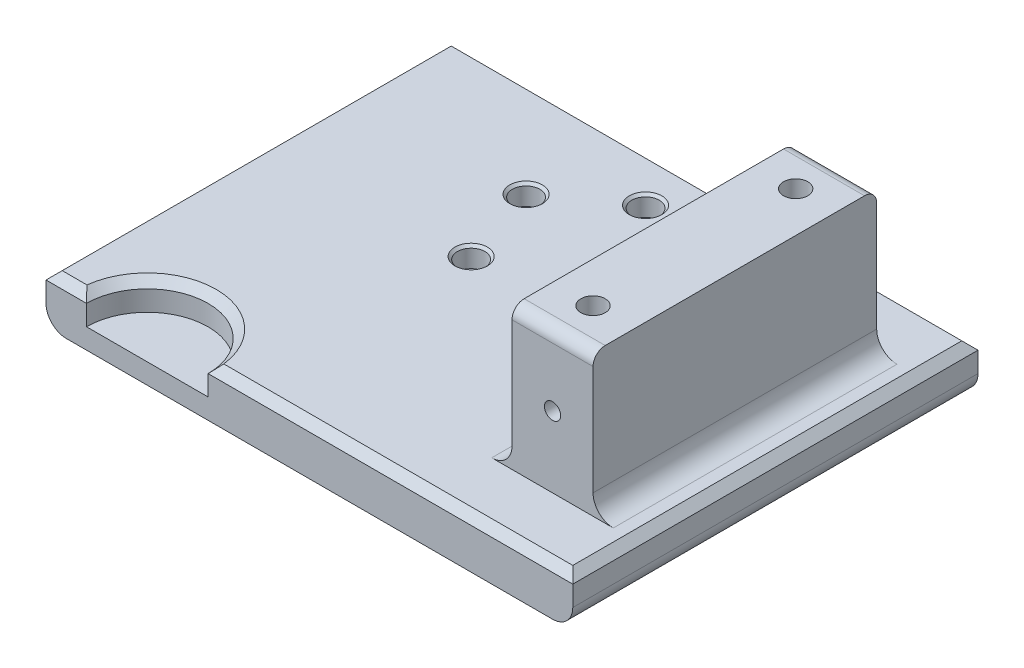
SolidWorks part; units mm, degrees
ref_plane "Front Plane" through (0, 0, 0) normal (0, 0, 1) x (1, 0, 0)
ref_plane "Top Plane" through (0, 0, 0) normal (0, 1, 0) x (1, 0, 0)
ref_plane "Right Plane" through (0, 0, 0) normal (1, 0, 0) x (0, 0, -1)
sketch "Sketch1" plane through (0, 0, 0) normal (0, 1, 0) x (1, 0, 0)
  line L1 (0, 0) -> (130, 0)
  line L2 (0, 0) -> (0, 100)
  line L3 (0, 100) -> (130, 100)
  line L4 (130, 0) -> (130, 100)
  dimension "D1" = 100
  dimension "D2" = 130
extrude "Boss-Extrude1" add sketch "Sketch1" along normal blind 12
sketch "Sketch2" plane through (0, 12, 0) normal (0, 1, 0) x (1, 0, 0)
  line L0 (0, 100) -> (0, 0) construction
  line L1 (60, 90) -> (132, 90)
  line L2 (60, 90) -> (60, 78)
  line L3 (60, 78) -> (132, 78)
  line L4 (132, 90) -> (132, 78)
  line L6 (130, 100) -> (0, 100) construction
  line L7 (130, 0) -> (130, 100) construction
  line L8 (46, 53) -> (118, 53)
  line L9 (46, 53) -> (46, 41)
  line L10 (46, 41) -> (118, 41)
  line L11 (118, 53) -> (118, 41)
  line L12 (96, 90) -> (96, 41) construction
  line L13 (78, 71.5) -> (114, 71.5)
  line L14 (78, 71.5) -> (78, 59.5)
  line L15 (78, 59.5) -> (114, 59.5)
  line L16 (114, 71.5) -> (114, 59.5)
  point P20 (96, 71.5)
  dimension "D1" = 60
  dimension "D2" = 72
  dimension "D3" = 10
  dimension "D4" = 12
  dimension "D5" = 12
  dimension "D6" = 72
  dimension "D7" = 25
  dimension "D8" = 12
  dimension "D9" = 6.5
  dimension "D10" = 6.5
  dimension "D11" = 18
sketch "Sketch3" plane through (0, 12, 0) normal (0, 1, 0) x (1, 0, 0)
  line L0 (0, 0) -> (130, 0) construction
  line L1 (10, 0) -> (40, 0)
  arc A0 (10, 0) -> (40, 0) centre (25, 0) cw
  dimension "D1" = 15
  dimension "D2" = 25
extrude "Cut-Extrude1" cut sketch "Sketch3" against normal blind 7
sketch "Sketch4" plane through (0, 12, 0) normal (0, 1, 0) x (1, 0, 0)
  line L0 (130, 100) -> (0, 100) construction
  line L1 (100, 85) -> (120, 85)
  line L2 (100, 85) -> (100, 15)
  line L3 (100, 15) -> (120, 15)
  line L4 (120, 85) -> (120, 15)
  line L5 (40, 0) -> (130, 0) construction
  line L6 (130, 0) -> (130, 100) construction
  dimension "D1" = 15
  dimension "D2" = 15
  dimension "D3" = 10
  dimension "D4" = 20
extrude "Boss-Extrude2" add sketch "Sketch4" along normal blind 35
ref_plane "Plane1" through (110, 0, 0) normal (-1, 0, 0) x (0, 0, 1)
sketch "Sketch5" plane through (110, 0, 0) normal (-1, 0, 0) x (0, 0, 1)
  line L0 (-85, 29.5) -> (-15, 29.5) construction
  line L1 (-85, 47) -> (-85, 12) construction
  line L2 (-15, 47) -> (-15, 12) construction
  line L4 (-85, 29.5) -> (-60, 29.5)
  line L5 (-85, 29.5) -> (-85, 37.5)
  line L6 (-85, 37.5) -> (-60, 37.5)
  line L7 (-60, 29.5) -> (-60, 37.5)
  line L8 (-60, 33.5) -> (-35, 33.5)
  line L9 (-60, 33.5) -> (-60, 29.5)
  line L10 (-60, 29.5) -> (-35, 29.5)
  line L11 (-35, 33.5) -> (-35, 29.5)
  line L12 (-35, 31.5) -> (-15, 31.5)
  line L13 (-35, 31.5) -> (-35, 29.5)
  line L14 (-35, 29.5) -> (-15, 29.5)
  line L15 (-15, 31.5) -> (-15, 29.5)
  dimension "D1" = 8
  dimension "D2" = 25
  dimension "D3" = 25
revolve "Cut-Revolve1" cut sketch "Sketch5" angle 360 about L0
fillet "Fillet1" radius 5 2 edges at (120, 12, -50) (100, 12, -50)
chamfer "Chamfer1" distance 2 angle 45 6 edges at (130, 12, -50) (65, 12, -100) (0, 12, -50) (5, 12, 0) (25, 12, -15) (85, 12, 0)
sketch "Sketch6" plane through (0, 12, 0) normal (0, 1, 0) x (1, 0, 0)
  line L0 (60, 70) -> (60, 87.9551) construction
  line L1 (60, 87.9551) -> (60, 70) construction
  line L2 (60, 70) -> (42.9237, 75.5484) construction
  line L3 (60, 70) -> (49.4463, 55.4741) construction
  line L4 (60, 70) -> (70.5537, 55.4741) construction
  line L5 (60, 70) -> (77.0763, 75.5484) construction
  line L6 (0, 0) -> (0, 100) construction
  line L7 (0, 100) -> (130, 100) construction
  circle A0 centre (60, 70) radius 17.9551
  point P2 (42.9237, 75.5484)
  point P3 (60, 70)
  point P4 (49.4463, 55.4741)
  point P5 (70.5537, 55.4741)
  point P6 (77.0763, 75.5484)
  dimension "D1" = 72
  dimension "D2" = 72
  dimension "D3" = 72
  dimension "D4" = 72
  dimension "D5" = 60
  dimension "D6" = 30
hole_wizard "M8 Tapped Hole1" positions "Sketch9" profile "Sketch10" tap size "M8" standard "AS"
sketch "Sketch9" plane through (0, 12, 0) normal (0, 1, 0) x (1, 0, 0)
  point P0 (42.9237, 75.5484)
  point P3 (60, 87.9551)
  point P6 (77.0763, 75.5484)
  point P9 (70.5537, 55.4741)
  point P12 (49.4463, 55.4741)
sketch "Sketch10" plane through (42.9237, 12, -75.5484) normal (1, 0, 0) x (0, 0, 1)
  line L0 (0, 0) -> (0, 7.0429)
  line L1 (0, 7.0429) -> (3.4, 5)
  line L2 (3.4, 5) -> (3.4, 0.625)
  line L3 (3.4, 0.625) -> (4.025, 0)
  line L5 (4.025, 0) -> (0, 0)
  line L6 (-3.4, 0.625) -> (-4.025, 0) construction
  line L10 (0, 7.0429) -> (-3.4, 5) construction
  line L11 (0, -6.35) -> (0, 107.95) construction
  dimension "Tap Drill Dia." = 6.8
  dimension "Tap Drill Depth" = 5
  dimension "Near C'Sink Dia." = 8.05
  dimension "Near C'Sink Angle" = 90
  dimension "Drill Angle" = 118
cosmetic thread "Hole Thread1" parameters "D1"=5, "D2"=8
cosmetic thread "Hole Thread2" parameters "D1"=5, "D2"=8
cosmetic thread "Hole Thread3" parameters "D1"=5, "D2"=8
cosmetic thread "Hole Thread4" parameters "D1"=5, "D2"=8
cosmetic thread "Hole Thread5" parameters "D1"=5, "D2"=8
sketch "Sketch13" plane through (0, 47, 0) normal (0, 1, 0) x (1, 0, 0)
  line L0 (110, 85) -> (110, 15) construction
  line L1 (125, 85) -> (95, 85) construction
  line L2 (100, 15) -> (120, 15) construction
  line L3 (120, 85) -> (100, 85) construction
  circle A0 centre (110, 75) radius 3
  circle A1 centre (110, 25) radius 3
  dimension "D1" = 6
  dimension "D2" = 10
  dimension "D3" = 10
extrude "Cut-Extrude2" cut sketch "Sketch13" against normal up to surface (35 mm away) up to face at (42.9237, 12, -71.5234)
fillet "Fillet2" radius 3 2 edges at (110, 47, -85) (110, 47, -15)
fillet "Fillet3" radius 5 2 edges at (0, 0, -50) (130, 0, -50)
